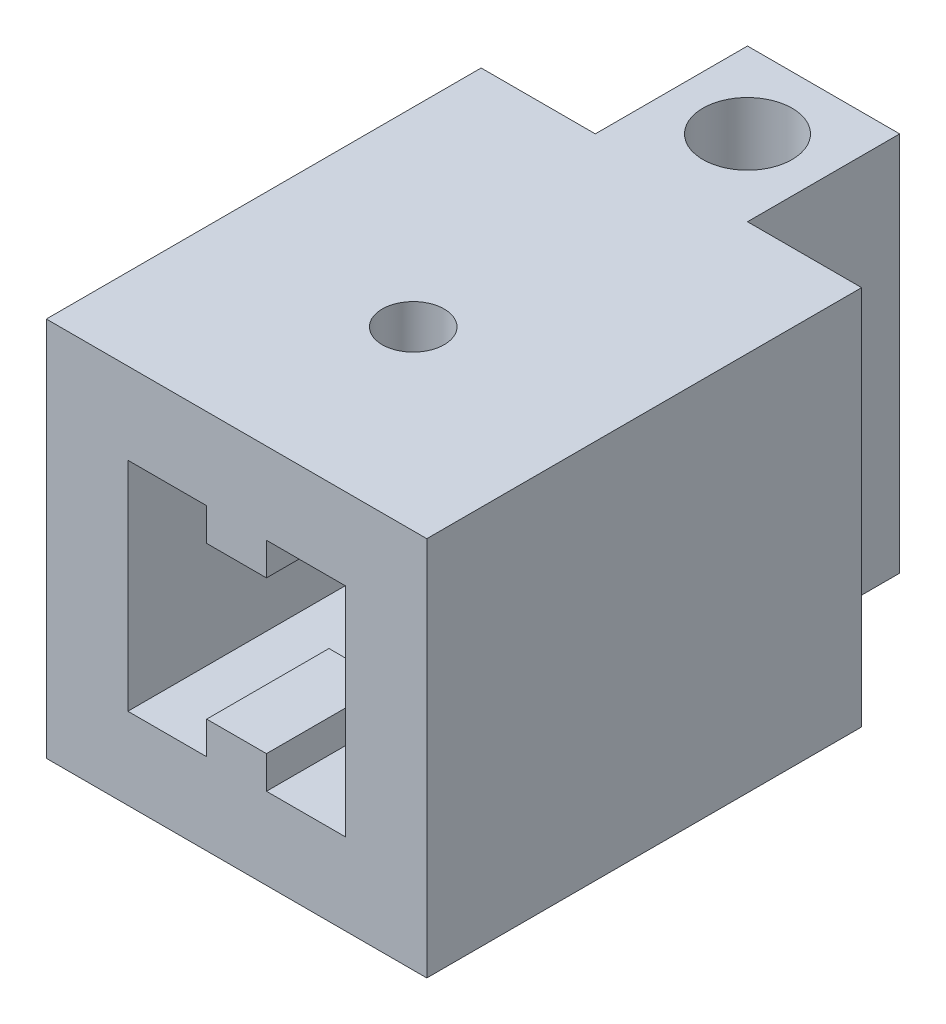
SolidWorks part; units mm, degrees
ref_plane "Спереди" through (0, 0, 0) normal (0, 0, 1) x (1, 0, 0)
ref_plane "Сверху" through (0, 0, 0) normal (0, 1, 0) x (1, 0, 0)
ref_plane "Справа" through (0, 0, 0) normal (1, 0, 0) x (0, 0, -1)
sketch "Эскиз1" plane through (0, 0, 0) normal (0, 0, 1) x (1, 0, 0)
  line L1 (-17.5, -17.5) -> (17.5, -17.5)
  line L2 (-17.5, -17.5) -> (-17.5, 17.5)
  line L3 (-17.5, 17.5) -> (17.5, 17.5)
  line L4 (17.5, -17.5) -> (17.5, 17.5)
  line L5 (-17.5, -17.5) -> (17.5, 17.5) construction
  line L6 (-17.5, 17.5) -> (17.5, -17.5) construction
  point P0 (0, 0)
  dimension "D1" = 35
  dimension "D2" = 35
extrude "Бобышка-Вытянуть1" add sketch "Эскиз1" against normal blind 40
sketch "Эскиз2" plane through (0, 0, 0) normal (0, 0, 1) x (1, 0, 0)
  line L0 (17.5, 17.5) -> (-17.5, 17.5) construction
  line L1 (-17.5, 17.5) -> (-17.5, -17.5) construction
  line L2 (-17.5, 10) -> (17.5, 10)
  line L3 (17.5, -17.5) -> (17.5, 17.5) construction
  line L4 (-10, 17.5) -> (-10, -17.5)
  line L5 (-17.5, -17.5) -> (17.5, -17.5) construction
  line L6 (10, 17.5) -> (10, -17.5)
  line L7 (-2.75, 10) -> (-2.75, -17.5)
  line L8 (2.75, 10) -> (2.75, -17.5)
  line L9 (-2.75, 10) -> (-2.75, 7)
  line L10 (-2.75, 7) -> (2.75, 7)
  line L11 (2.75, 7) -> (2.75, 10)
  line L12 (-17.5, -10) -> (17.5, -10)
  line L13 (-2.75, -7) -> (2.75, -7)
  line L14 (-10, -10) -> (-2.75, -10)
  line L15 (-2.75, -10) -> (-2.75, -7)
  line L16 (2.75, -7) -> (2.75, -10)
  line L17 (2.75, -10) -> (10, -10)
  line L18 (-10, 10) -> (-10, -10)
  line L19 (10, 10) -> (10, -10)
  line L20 (10, 2.75) -> (-17.5, 2.75)
  line L21 (10, -2.75) -> (-17.5, -2.75)
  line L22 (-10, 10) -> (-10, 2.75)
  line L23 (-10, 2.75) -> (-7, 2.75)
  line L24 (-7, 2.75) -> (-7, -2.75)
  line L25 (10, 10) -> (10, 2.75)
  line L26 (7, 2.75) -> (7, -2.75)
  line L27 (7, -2.75) -> (10, -2.75)
  point P0 (-10, 17.5)
  point P1 (10, 17.5)
  point P4 (-17.5, 10)
  point P19 (-2.75, 10)
  point P20 (-10, 10)
  point P21 (10, 10)
  point P22 (2.75, 10)
  point P25 (-2.75, 7)
  point P28 (-17.5, -10)
  point P34 (-2.75, -7)
  point P35 (-2.75, -10)
  point P44 (10, 2.75)
  point P45 (-10, 10)
  point P46 (-10, 10)
  point P47 (-10, -5.6206)
  point P48 (-10, 2.3032)
  point P49 (-10, 10)
  point P50 (-10, -10)
  point P51 (-10, 10)
  point P52 (-10, 2.3032)
  point P53 (-10, 10)
  point P54 (10, -2.75)
  point P59 (-7, 2.75)
  point P60 (7, 2.75)
  dimension "D1" = 7.5
  dimension "D2" = 7.5
  dimension "D3" = 7.5
  dimension "D4" = 7.25
  dimension "D5" = 5.5
  dimension "D6" = 3
  dimension "D7" = 7.5
  dimension "D8" = 3
  dimension "D9" = 7.25
  dimension "D10" = 7.25
  dimension "D11" = 3
  dimension "D12" = 3
extrude "Вырез-Вытянуть4" cut sketch "Эскиз2" against normal blind 32.5 contours L21 L8 L20 L7 | L20 L8 L10 L7 | L8 L21 L7 L13 | L6 L21 L8 L12 | L20 L6 L2 L8 | L20 L7 L2 L4 | L7 L21 L4 L12 | L20 L24 L21 L7 | L24 L20 L18 L21 | L26 L20 L8 L21 | L20 L26 L21 L19
sketch "Эскиз3" plane through (0, 7, 0) normal (0, -1, 0) x (1, 0, 0)
  line L0 (2.75, -32.5) -> (2.75, 0) construction
  line L1 (2.75, -11.25) -> (2.75, -21.25)
  line L2 (2.75, -21.25) -> (-2.75, -21.25)
  line L3 (-2.75, -32.5) -> (-2.75, 0) construction
  line L4 (-2.75, -21.25) -> (-2.75, -11.25)
  line L5 (-2.75, -11.25) -> (2.75, -11.25)
  point P0 (2.75, -11.25)
  point P1 (2.75, -21.25)
  dimension "D1" = 11.25
  dimension "10" = 10
extrude "Вырез-Вытянуть5" cut sketch "Эскиз3" against normal blind 3
sketch "Эскиз4" plane through (0, -7, 0) normal (0, 1, 0) x (1, 0, 0)
  line L0 (2.75, 32.5) -> (2.75, 0) construction
  line L1 (2.75, 11.25) -> (2.75, 21.25)
  line L2 (2.75, 21.25) -> (-2.75, 21.25)
  line L3 (-2.75, 32.5) -> (-2.75, 0) construction
  line L4 (-2.75, 21.25) -> (-2.75, 11.25)
  line L5 (-2.75, 11.25) -> (2.75, 11.25)
  point P0 (2.75, 11.25)
  point P1 (2.75, 21.25)
  dimension "D1" = 11.25
  dimension "D2" = 10
extrude "Вырез-Вытянуть6" cut sketch "Эскиз4" against normal blind 3
sketch "Эскиз5" plane through (0, 17.5, 0) normal (0, 1, 0) x (1, 0, 0)
  line L0 (0, 0) -> (0, 40)
  line L1 (17.5, 0) -> (-17.5, 0) construction
  line L2 (17.5, 40) -> (-17.5, 40) construction
  circle A0 centre (0, 16.25) radius 2.85
  point P6 (0, 16.25)
  dimension "D1" = 16.25
extrude "Вырез-Вытянуть7" cut sketch "Эскиз5" against normal through all contours L0 A0 | L0 A0
sketch "Эскиз6" plane through (0, 0, -40) normal (0, 0, -1) x (-1, 0, 0)
  line L0 (-17.5, 17.5) -> (17.5, 17.5) construction
  line L1 (7, 17.5) -> (-7, 17.5)
  line L2 (-7, 17.5) -> (-7, -17.5)
  line L3 (17.5, -17.5) -> (-17.5, -17.5) construction
  line L4 (-7, -17.5) -> (7, -17.5)
  line L5 (7, -17.5) -> (7, 17.5)
  point P0 (-7, 17.5)
  point P1 (7, 17.5)
  point P4 (0, 17.5)
  dimension "D1" = 7
  dimension "14" = 14
extrude "Бобышка-Вытянуть2" add sketch "Эскиз6" along normal blind 14
sketch "Эскиз7" plane through (0, 17.5, 0) normal (0, 1, 0) x (1, 0, 0)
  line L0 (7, 40) -> (-7, 40)
  line L1 (0, 40) -> (0, 54)
  line L2 (-7, 54) -> (7, 54) construction
  circle A0 centre (0, 47) radius 4.03
extrude "Вырез-Вытянуть8" cut sketch "Эскиз7" against normal through all contours L1 A0 | L1 A0
sketch "Эскиз8" plane through (0, -17.5, 0) normal (0, -1, 0) x (1, 0, 0)
  line L0 (7, -40) -> (-7, -40)
  line L1 (0, -40) -> (0, -54)
  line L2 (7, -54) -> (-7, -54) construction
  point P0 (7, -40)
  point P2 (-7, -40)
  point P6 (0, -40)
sketch "Эскиз13" plane through (0, -17.5, 0) normal (0, -1, 0) x (1, 0, 0)
  circle A0 centre (0, -47) radius 4.1
  point P0 (0, -47)
extrude "Вырез-Вытянуть9" cut sketch "Эскиз13" against normal through all
sketch "Эскиз19" plane through (0, -17.5, 0) normal (0, -1, 0) x (1, 0, 0)
  point P0 (0, -47)
